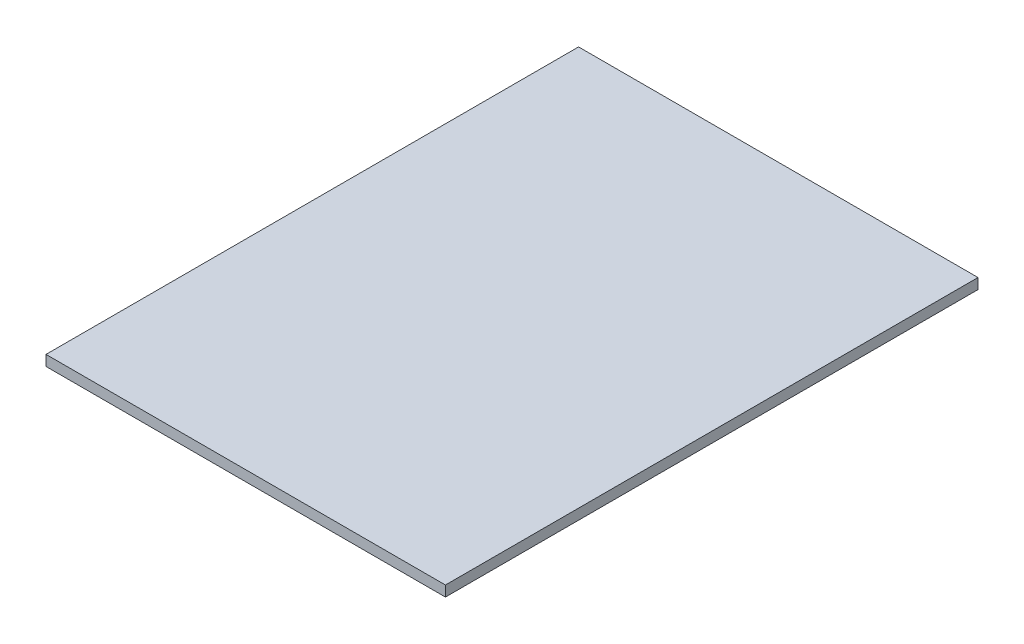
SolidWorks part; units mm, degrees
ref_plane "Front Plane" through (0, 0, 0) normal (0, 0, 1) x (1, 0, 0)
ref_plane "Top Plane" through (0, 0, 0) normal (0, 1, 0) x (1, 0, 0)
ref_plane "Right Plane" through (0, 0, 0) normal (1, 0, 0) x (0, 0, -1)
sketch "Sketch1" plane through (0, 0, 0) normal (0, 0, 1) x (1, 0, 0)
  line L1 (-71.5333, 1.3214) -> (4.6667, 1.3214)
  line L2 (-71.5333, 1.3214) -> (-71.5333, -0.6786)
  line L3 (-71.5333, -0.6786) -> (4.6667, -0.6786)
  line L4 (4.6667, 1.3214) -> (4.6667, -0.6786)
  dimension "D1" = 2
  dimension "D2" = 76.2
extrude "Boss-Extrude1" add sketch "Sketch1" along normal blind 101.6
